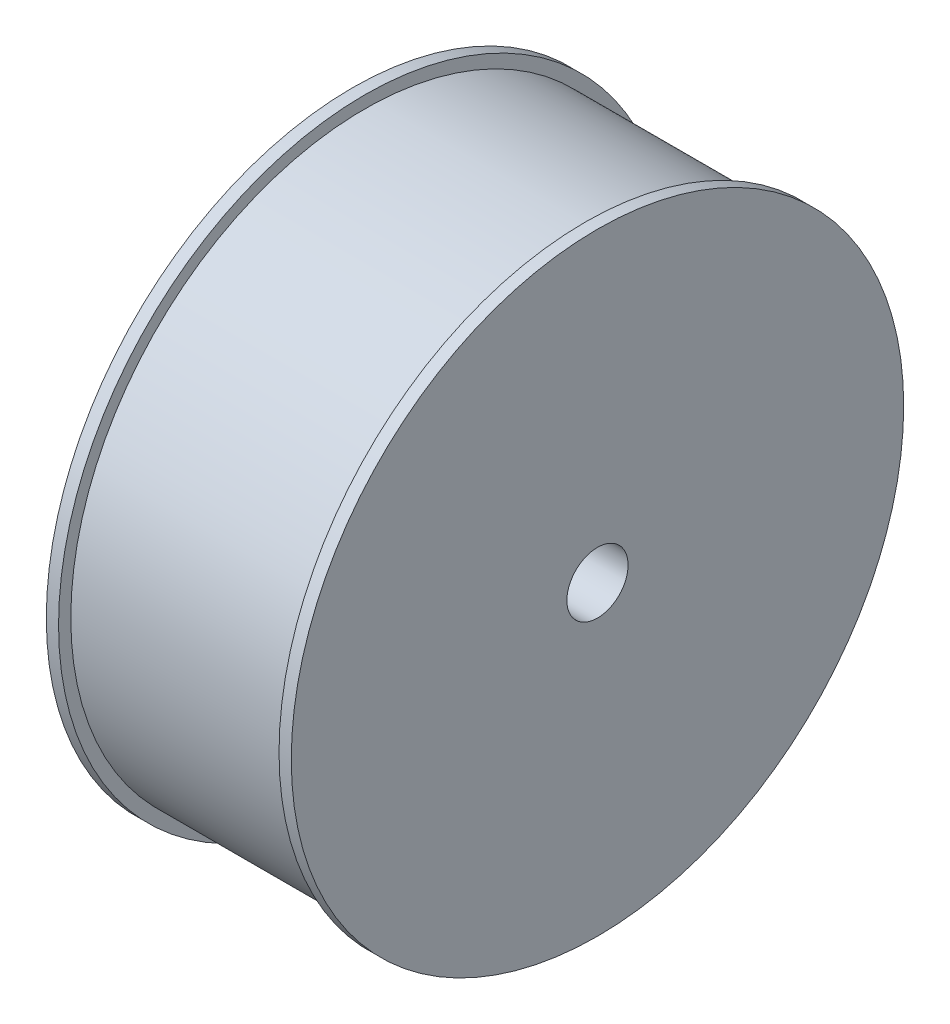
SolidWorks part; units mm, degrees
material "PTFE (general)"
ref_plane "Front Plane" through (0, 0, 0) normal (0, 0, 1) x (1, 0, 0)
ref_plane "Top Plane" through (0, 0, 0) normal (0, 1, 0) x (1, 0, 0)
ref_plane "Right Plane" through (0, 0, 0) normal (1, 0, 0) x (0, 0, -1)
sketch "Sketch2" plane through (0, 0, 0) normal (0, 0, 1) x (1, 0, 0)
  line L0 (-50, 12.5) -> (-50, 125)
  line L1 (-50, 125) -> (-45, 125)
  line L2 (-45, 125) -> (-45, 120)
  line L3 (-45, 120) -> (45, 120)
  line L4 (45, 120) -> (45, 125)
  line L5 (45, 125) -> (50, 125)
  line L6 (50, 125) -> (50, 12.5)
  line L7 (50, 12.5) -> (-50, 12.5)
  line L8 (0, 0) -> (0, 84.6457) construction
  line L9 (-72.6397, 0) -> (81.4482, 0) construction
  dimension "D1" = 250
  dimension "D2" = 25
  dimension "D3" = 5
  dimension "D4" = 5
  dimension "D5" = 5
  dimension "D6" = 100
revolve "Revolve1" add sketch "Sketch2" angle 360 about L9
